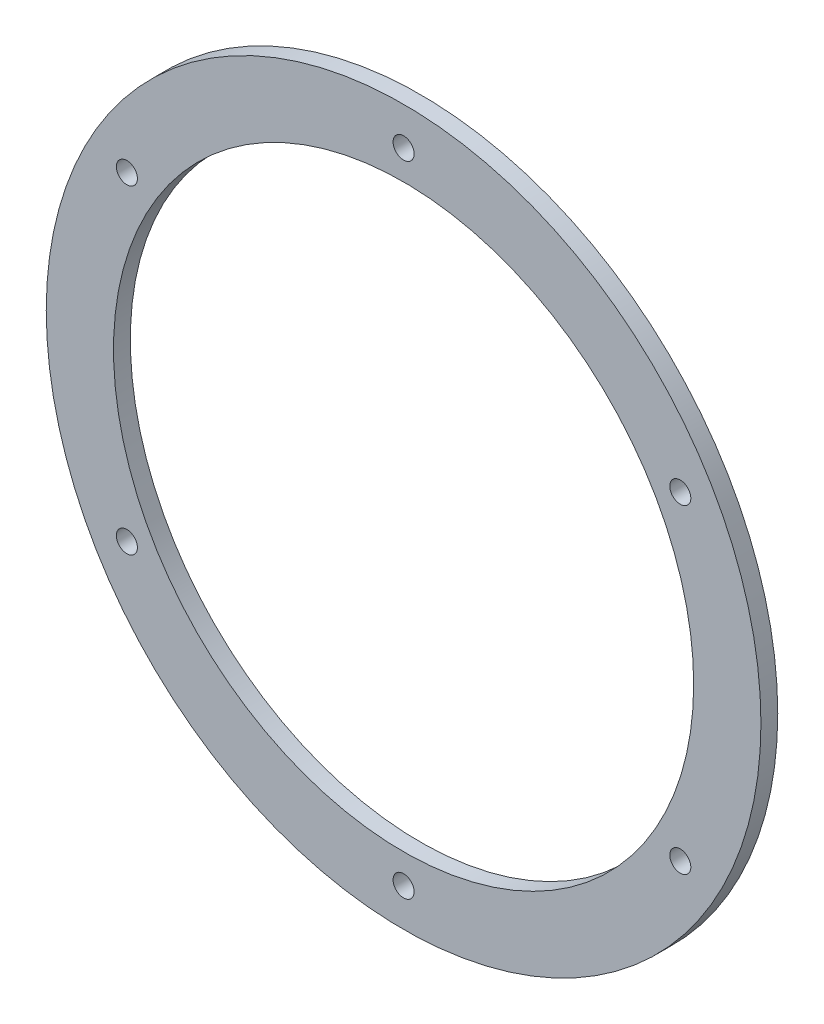
SolidWorks part; units mm, degrees
ref_plane "Front" through (0, 0, 0) normal (0, 0, 1) x (1, 0, 0)
ref_plane "Top" through (0, 0, 0) normal (0, 1, 0) x (1, 0, 0)
ref_plane "Right" through (0, 0, 0) normal (1, 0, 0) x (0, 0, -1)
sketch "Эскиз1" plane through (0, 0, 0) normal (0, 0, 1) x (1, 0, 0)
  circle A0 centre (0, 0) radius 42.5
  circle A1 centre (0, 0) radius 34.5
  dimension "D1" = 85
  dimension "D2" = 69
extrude "Уплотнительное кольцо" add sketch "Эскиз1" along normal blind 2
sketch "Эскиз3" plane through (0, 0, 2) normal (0, 0, 1) x (1, 0, 0)
  circle A2 centre (0, 38) radius 1.25
  dimension "D1" = 2.5
  dimension "D2" = 38
extrude "Под шуруп" cut sketch "Эскиз3" against normal through all
pattern_circular "Под шурупы по окружности" count 6 over 360 about axis through (0, 0, 0) along (0, 0, 1) of "Под шуруп"
